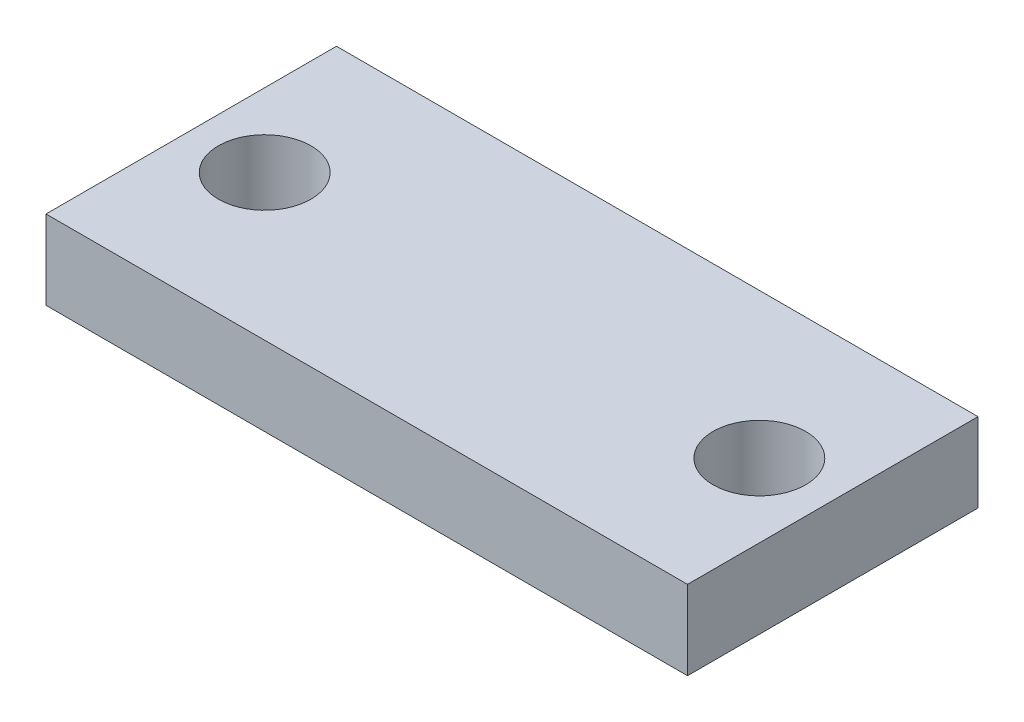
SolidWorks part; units mm, degrees
material "Thornel Mat VMA"
ref_plane "前视基准面" through (0, 0, 0) normal (0, 0, 1) x (1, 0, 0)
ref_plane "上视基准面" through (0, 0, 0) normal (0, 1, 0) x (1, 0, 0)
ref_plane "右视基准面" through (0, 0, 0) normal (1, 0, 0) x (0, 0, -1)
sketch "草图1" plane through (0, 0, 0) normal (0, 1, 0) x (1, 0, 0)
  line L1 (-16.21, -7.34) -> (16.21, -7.34)
  line L2 (-16.21, -7.34) -> (-16.21, 7.34)
  line L3 (-16.21, 7.34) -> (16.21, 7.34)
  line L4 (16.21, -7.34) -> (16.21, 7.34)
  line L5 (-16.21, -7.34) -> (16.21, 7.34) construction
  line L6 (-16.21, 7.34) -> (16.21, -7.34) construction
  point P0 (0, 0)
  dimension "D1" = 32.42
  dimension "D2" = 14.68
extrude "凸台-拉伸1" add sketch "草图1" along normal blind 4
sketch "草图2" plane through (0, 4, 0) normal (0, 1, 0) x (1, 0, 0)
  line L0 (0, -7.34) -> (0, 7.34) construction
  line L1 (16.21, 7.34) -> (-16.21, 7.34) construction
  line L2 (-16.21, 0) -> (16.21, 0) construction
  line L3 (16.21, -7.34) -> (16.21, 7.34) construction
  circle A0 centre (12.5, 0) radius 2.34
  circle A1 centre (-12.5, 0) radius 2.34
  point P6 (0, 0)
  point P12 (0, 0)
  dimension "D1" = 4.68
  dimension "D2" = 25
extrude "切除-拉伸1" cut sketch "草图2" against normal through all
